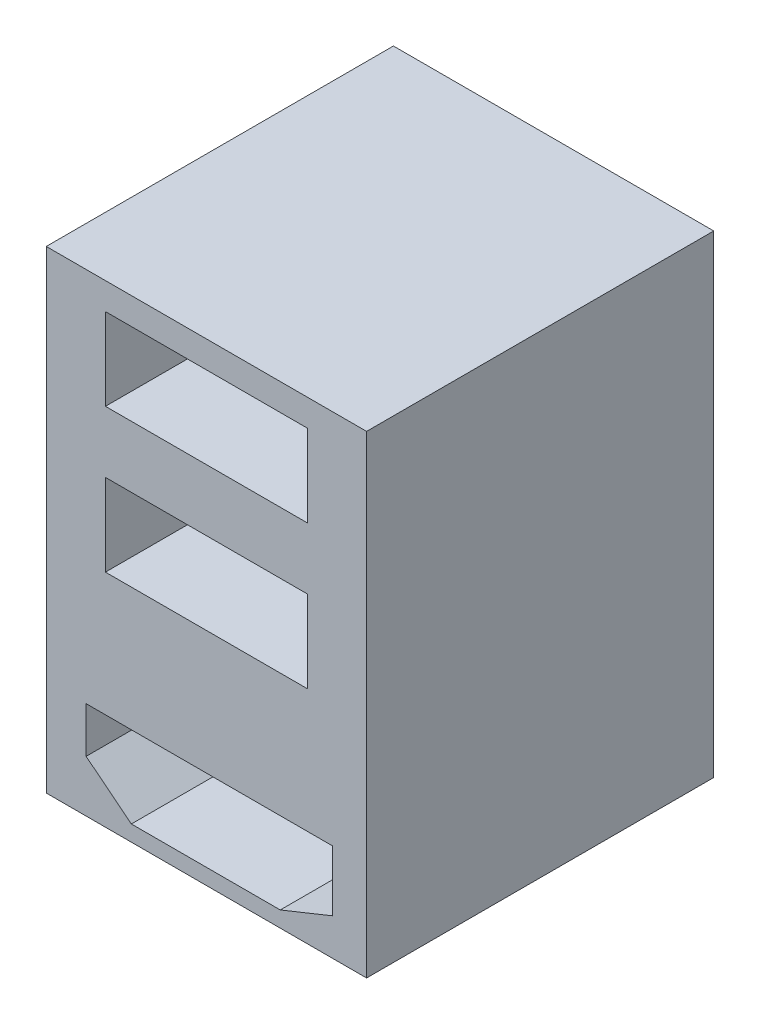
SolidWorks part; units mm, degrees
ref_plane "Спереди" through (0, 0, 0) normal (0, 0, 1) x (1, 0, 0)
ref_plane "Сверху" through (0, 0, 0) normal (0, 1, 0) x (1, 0, 0)
ref_plane "Справа" through (0, 0, 0) normal (1, 0, 0) x (0, 0, -1)
sketch "Эскиз1" plane through (0, 0, 0) normal (0, 0, 1) x (1, 0, 0)
  line L0 (160, 640) -> (800, 640) construction
  line L1 (-1218.8215, 54.0139) -> (-1048.8215, 54.0139) construction
  line L2 (103.3919, 165.2377) -> (729.0292, 165.2377) construction
  line L7 (114.6742, 106.7984) -> (191.8742, 106.7984) construction
  line L8 (124.8864, 106.9603) -> (124.8864, 76.9603) construction
  line L9 (114.7364, 106.9603) -> (135.0364, 106.9603)
  line L10 (114.7364, 106.9603) -> (114.7364, 76.9603)
  line L11 (114.7364, 76.9603) -> (135.0364, 76.9603)
  line L12 (135.0364, 106.9603) -> (135.0364, 76.9603)
  line L13 (131.2864, 90.9603) -> (118.4864, 90.9603)
  line L14 (131.2864, 100.0603) -> (118.4864, 100.0603)
  line L15 (131.2864, 100.0603) -> (131.2864, 105.2603)
  line L16 (131.2864, 105.2603) -> (118.4864, 105.2603)
  line L17 (118.4864, 100.0603) -> (118.4864, 105.2603)
  line L18 (131.2864, 100.0603) -> (118.4864, 105.2603) construction
  line L19 (131.2864, 105.2603) -> (118.4864, 100.0603) construction
  line L24 (131.2864, 90.9603) -> (131.2864, 96.1603)
  line L25 (131.2864, 96.1603) -> (118.4864, 96.1603)
  line L26 (129.5666, 77.9603) -> (120.1295, 77.9603)
  line L27 (132.8868, 79.2966) -> (132.8868, 83.1307)
  line L28 (132.8868, 83.1307) -> (117.263, 83.1307)
  line L29 (117.263, 80.238) -> (117.263, 83.1307)
  line L30 (130.3251, 78.2656) -> (117.263, 83.1307) construction
  line L31 (132.8868, 83.1307) -> (119.5704, 78.4046) construction
  line L32 (118.4864, 90.9603) -> (118.4864, 96.1603)
  line L33 (129.5666, 77.9603) -> (132.8868, 79.2966)
  line L38 (119.8242, 80.5488) -> (129.9485, 79.9338) construction
  line L39 (119.8242, 79.9338) -> (129.9485, 80.5488) construction
  line L44 (119.5831, 95.8633) -> (130.1896, 94.658) construction
  line L45 (119.5831, 94.658) -> (130.1896, 95.8633) construction
  line L50 (119.5831, 104.4851) -> (130.1896, 103.2447) construction
  line L51 (119.5831, 103.2447) -> (130.1896, 104.4851) construction
  line L52 (117.263, 80.238) -> (120.1295, 77.9603)
  point P14 (124.8864, 102.6603)
  point P19 (124.8864, 94.341)
  point P20 (124.8864, 95.2607)
  point P24 (124.8864, 80.2913)
  point P34 (124.8864, 103.8649)
  point P35 (124.8864, 80.2413)
  dimension "D1" = 170
  dimension "D2" = 20.3
  dimension "D3" = 77.2
  dimension "D4" = 30
  dimension "D5" = 5.2
  dimension "D6" = 12.8
  dimension "D7" = 1.7
  dimension "D9" = 16
  dimension "D10" = 1
  dimension "D8" = 2
extrude "Бобышка-Вытянуть1" add sketch "Эскиз1" against normal blind 10
sketch "Эскиз2" plane through (0, 0, -10) normal (0, 0, -1) x (-1, 0, 0)
  line L0 (-114.7364, 76.9603) -> (-135.0364, 76.9603) construction
  line L1 (-135.0364, 106.9603) -> (-114.7364, 106.9603)
  line L2 (-135.0364, 106.9603) -> (-135.0364, 76.9603)
  line L3 (-135.0364, 76.9603) -> (-114.7364, 76.9603)
  line L4 (-114.7364, 106.9603) -> (-114.7364, 76.9603)
  line L5 (-114.7364, 106.9603) -> (-114.7364, 76.9603) construction
extrude "Бобышка-Вытянуть2" add sketch "Эскиз2" along normal blind 12
